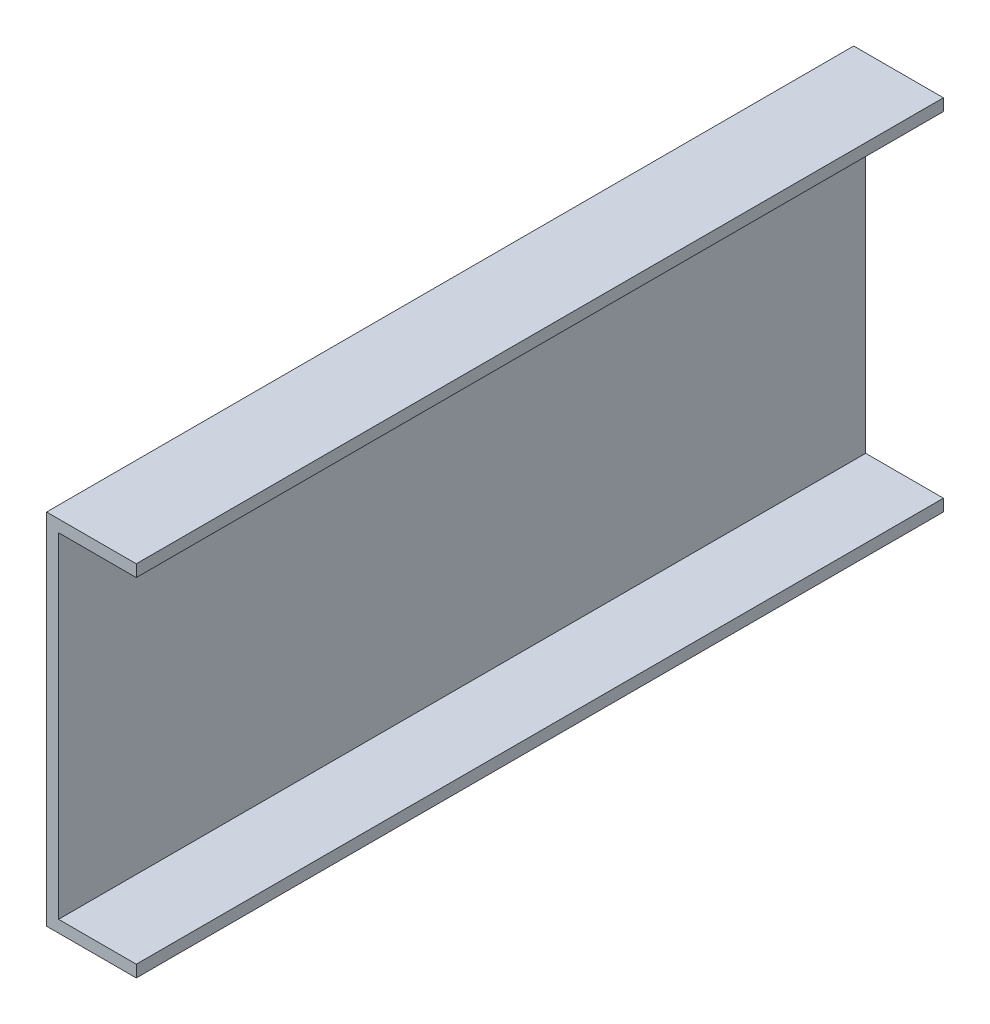
SolidWorks part; units mm, degrees
material "6061 Alloy"
ref_plane "Front Plane" through (0, 0, 0) normal (0, 0, 1) x (1, 0, 0)
ref_plane "Top Plane" through (0, 0, 0) normal (0, 1, 0) x (1, 0, 0)
ref_plane "Right Plane" through (0, 0, 0) normal (1, 0, 0) x (0, 0, -1)
sketch "Sketch1" plane through (0, 0, 0) normal (0, 0, 1) x (1, 0, 0)
  line L0 (-74.3301, 44.6448) -> (-74.3301, -31.5552)
  line L1 (-74.3301, -31.5552) -> (-55.2801, -31.5552)
  line L2 (-74.3301, 44.6448) -> (-55.2801, 44.6448)
  dimension "D1" = 76.2
  dimension "D2" = 19.05
  dimension "D3" = 19.05
extrude "Extrude-Thin1" add sketch "Sketch1" along normal blind 171.45 thin thin type one direction wall 2.54
